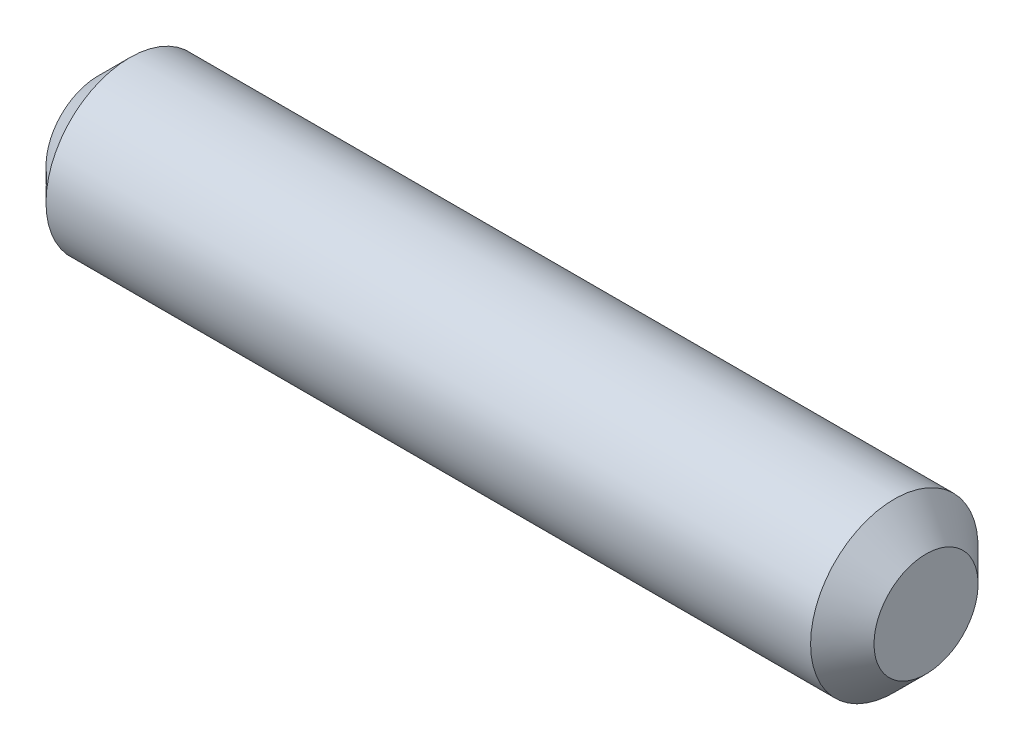
SolidWorks part; units mm, degrees
ref_plane "Front Plane" through (0, 0, 0) normal (0, 0, 1) x (1, 0, 0)
ref_plane "Top Plane" through (0, 0, 0) normal (0, 1, 0) x (1, 0, 0)
ref_plane "Right Plane" through (0, 0, 0) normal (1, 0, 0) x (0, 0, -1)
sketch "Sketch1" plane through (0, 0, 0) normal (1, 0, 0) x (0, 0, -1)
  circle A0 centre (0, 0) radius 1.585
  dimension "D1" = 3.17
extrude "Boss-Extrude1" add sketch "Sketch1" along normal mid plane 15.67
chamfer "Chamfer1" distance 0.6 angle 45 2 edges at (7.835, 0, -1.585) (-7.835, 0, -1.585)
